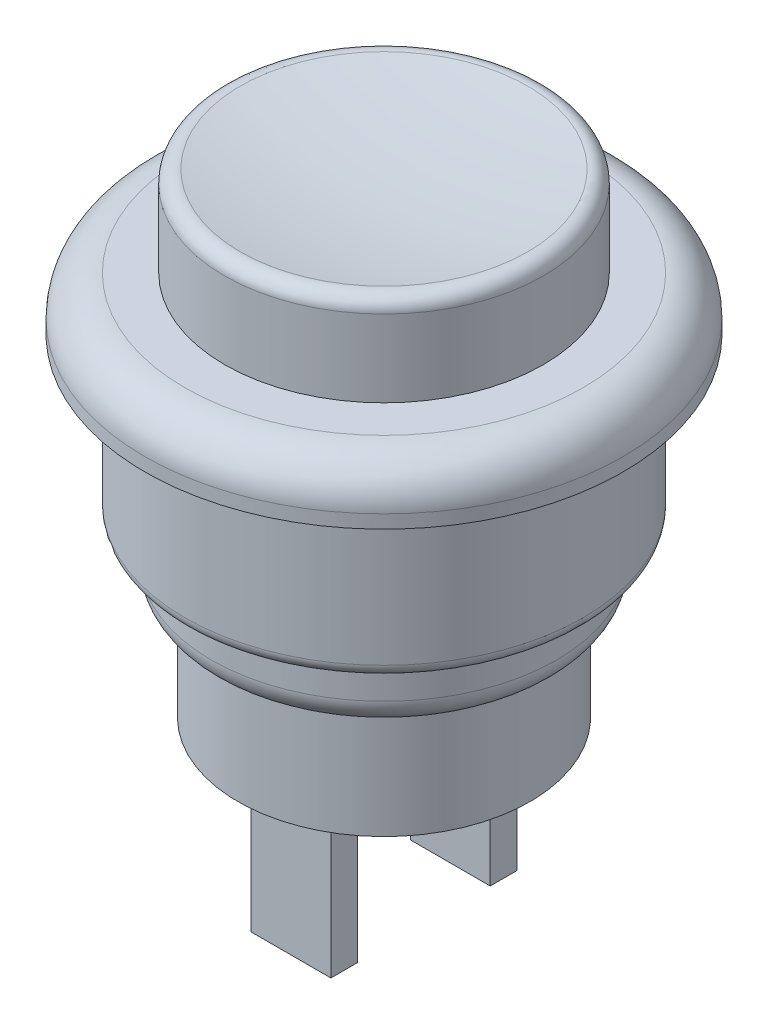
SolidWorks part; units mm, degrees
ref_plane "Front Plane" through (0, 0, 0) normal (0, 0, 1) x (1, 0, 0)
ref_plane "Top Plane" through (0, 0, 0) normal (0, 1, 0) x (1, 0, 0)
ref_plane "Right Plane" through (0, 0, 0) normal (1, 0, 0) x (0, 0, -1)
sketch "Sketch1" plane through (0, 0, 0) normal (0, 0, 1) x (1, 0, 0)
  line L0 (0, -9) -> (0, 9) construction
  line L1 (0, 9) -> (6, 9) construction
  line L2 (6, 9) -> (6, 5.5)
  line L3 (6, 5.5) -> (9, 5.5)
  line L4 (9, 5.5) -> (9, 3.5)
  line L5 (9, 3.5) -> (7.5, 3.5)
  line L8 (6.5, -2.5) -> (6.5, -4.5)
  line L9 (6.5, -4.5) -> (5.5, -5)
  line L10 (5.5, -5) -> (5.5, -9)
  line L11 (5.5, -9) -> (0, -9)
  line L12 (7.5, 3.5) -> (7.5, -2.5)
  line L13 (7.5, -2.5) -> (6.5, -2.5)
  line L14 (0, 9) -> (-6, 9) construction
  line L15 (0, 8.3961) -> (0, -9)
  arc A0 (0, 8.3961) -> (6, 9) centre (0, 38.5041) ccw
  point P4 (0, 0)
  dimension "D1" = 18
  dimension "D2" = 3.5
  dimension "D3" = 6
  dimension "D4" = 3
  dimension "D5" = 2
  dimension "D6" = 1.5
  dimension "D7" = 1
  dimension "D8" = 6
  dimension "D9" = 5.5
  dimension "D10" = 4
  dimension "D11" = 2
revolve "Revolve1" add sketch "Sketch1" angle 360 about L0
fillet "Fillet1" radius 1.5 1 edges at (0, 5.5, -9)
fillet "Fillet2" radius 0.5 1 edges at (0, 9, -6)
fillet "Fillet3" radius 1 1 edges at (0, -4.5, -6.5)
fillet "Fillet4" radius 0.5 1 edges at (0, -2.5, -7.5)
sketch "Sketch2" plane through (0, -9, 0) normal (0, -1, 0) x (1, 0, 0)
  line L0 (0, 5.5) -> (0, 3.5) construction
  line L1 (-1.5, 3.5) -> (1.5, 3.5)
  line L2 (-1.5, 3.5) -> (-1.5, 2.5)
  line L3 (-1.5, 2.5) -> (1.5, 2.5)
  line L4 (1.5, 3.5) -> (1.5, 2.5)
  line L5 (-1.5, -3.5) -> (1.5, -3.5)
  line L6 (-1.5, -3.5) -> (-1.5, -2.5)
  line L7 (-1.5, -2.5) -> (1.5, -2.5)
  line L8 (1.5, -3.5) -> (1.5, -2.5)
  line L9 (0, -3.5) -> (0, -5.5) construction
  line L10 (0, 0) -> (0, -2.5) construction
  circle A0 centre (0, 0) radius 5.5 construction
  circle A1 centre (0, 0) radius 5.5 construction
  point P21 (0, 0)
  dimension "D1" = 3
  dimension "D2" = 1
  dimension "D3" = 5
extrude "Boss-Extrude1" add sketch "Sketch2" along normal blind 6
